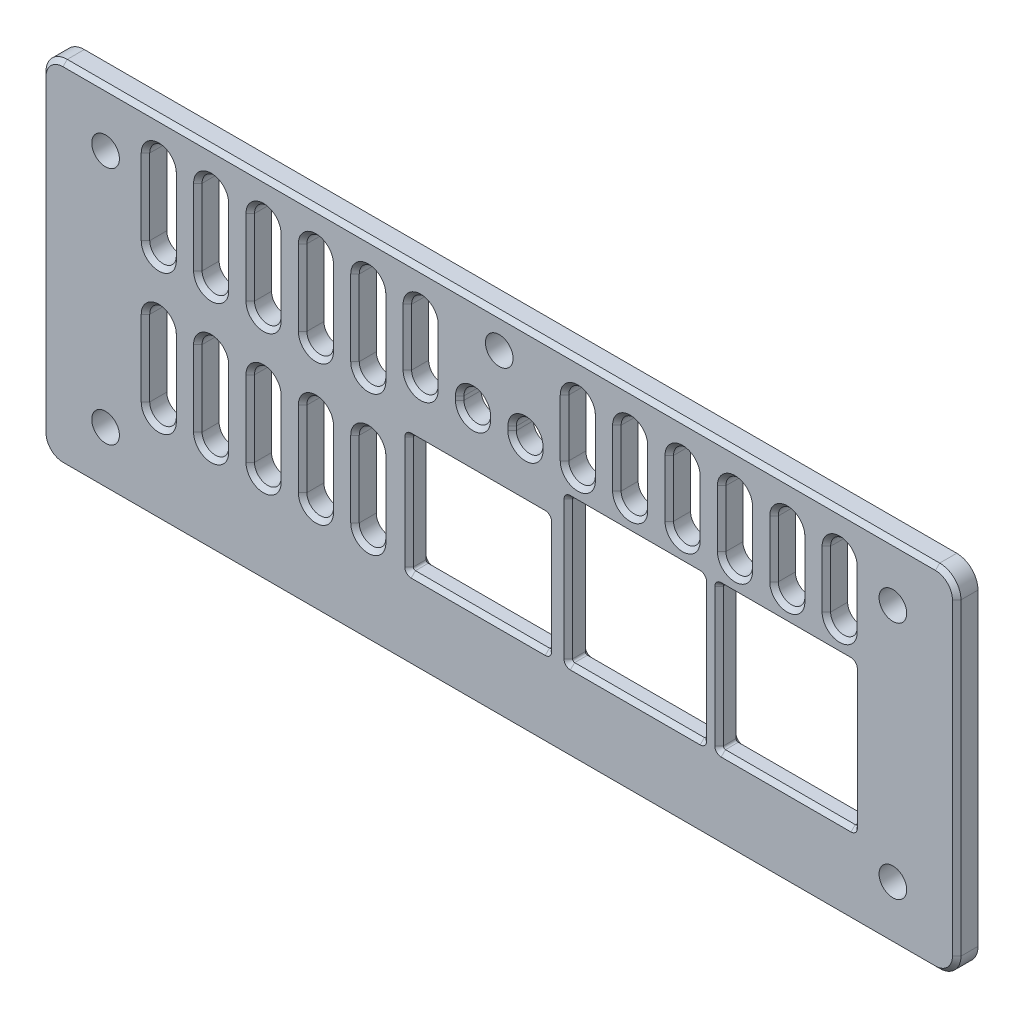
SolidWorks part; units mm, degrees
ref_plane "Plane XZ" through (0, 0, 0) normal (0, 0, 1) x (1, 0, 0)
ref_plane "Plane XY" through (0, 0, 0) normal (0, 1, 0) x (1, 0, 0)
ref_plane "Plane YZ" through (0, 0, 0) normal (1, 0, 0) x (0, 0, -1)
sketch "Sketch1" plane through (0, 0, 0) normal (0, 0, 1) x (1, 0, 0)
  line L0 (-55.88, -14.2875) -> (55.88, -14.2875) construction
  line L1 (-55.88, 22.225) -> (55.88, 22.225) construction
  line L2 (-55.88, 22.225) -> (-55.88, -22.225) construction
  line L3 (-55.88, -22.225) -> (55.88, -22.225) construction
  line L4 (55.88, 22.225) -> (55.88, -22.225) construction
  line L5 (0, 0) -> (0, -14.2875) construction
  line L6 (0, 0) -> (-55.88, 0) construction
  line L7 (-54.61, 20.955) -> (54.61, 20.955)
  line L8 (54.61, 20.955) -> (54.61, -20.955)
  line L9 (-54.61, -20.955) -> (54.61, -20.955)
  line L10 (-54.61, 20.955) -> (-54.61, -20.955)
  dimension "D1" = 111.76
  dimension "D2" = 44.45
  dimension "D3" = 14.2875
  dimension "D4" = 1.27
extrude "Boss-Extrude1" add sketch "Sketch1" along normal blind 2.54
sketch "Sketch4" plane through (0, 0, 2.54) normal (0, 0, 1) x (1, 0, 0)
  line L0 (-46.99, 0) -> (46.99, 0) construction
  line L1 (-46.99, 14.2875) -> (46.99, 14.2875) construction
  line L2 (-46.99, 14.2875) -> (-46.99, -14.2875) construction
  line L3 (-46.99, -14.2875) -> (46.99, -14.2875) construction
  line L4 (46.99, 14.2875) -> (46.99, -14.2875) construction
  circle A0 centre (-46.99, 14.2875) radius 1.651
  circle A1 centre (-46.99, -14.2875) radius 1.651
  circle A2 centre (46.99, -14.2875) radius 1.651
  circle A3 centre (46.99, 14.2875) radius 1.651
  dimension "D1" = 3.302
  dimension "D4" = 3.302
  dimension "D2" = 93.98
  dimension "D3" = 28.575
extrude "Cut-Extrude2" cut sketch "Sketch4" against normal through all and the other way through all
fillet "Fillet1" radius 2.54 4 edges at (54.61, 20.955, 1.27) (54.61, -20.955, 1.27) (-54.61, -20.955, 1.27) (-54.61, 20.955, 1.27)
sketch "Sketch3" plane through (0, 0, 2.54) normal (0, 0, 1) x (1, 0, 0)
  line L0 (15.24, -11.1252) -> (15.24, -12.3825) construction
  line L1 (-12.76, -11.1252) -> (43.24, -11.1252) construction
  line L2 (-12.76, -11.1252) -> (-12.76, -12.3825) construction
  line L3 (-12.76, -12.3825) -> (43.24, -12.3825) construction
  line L4 (43.24, -11.1252) -> (43.24, -12.3825) construction
  line L5 (-55.88, -14.2875) -> (55.88, -14.2875) construction
  line L6 (16.24, 5.8928) -> (16.24, -11.1252) construction
  line L7 (8.239, 5.8928) -> (24.241, 5.8928)
  line L8 (8.239, 5.8928) -> (8.239, -11.1252)
  line L9 (8.239, -11.1252) -> (24.241, -11.1252)
  line L10 (24.241, 5.8928) -> (24.241, -11.1252)
  line L11 (26.239, 5.8928) -> (42.241, 5.8928)
  line L12 (26.239, 5.8928) -> (26.239, -11.1252)
  line L13 (26.239, -11.1252) -> (42.241, -11.1252)
  line L14 (42.241, 5.8928) -> (42.241, -11.1252)
  line L15 (-10.765, 2.8448) -> (5.745, 2.8448)
  line L16 (-10.765, 2.8448) -> (-10.765, -11.1252)
  line L17 (-10.765, -11.1252) -> (5.745, -11.1252)
  line L18 (5.745, 2.8448) -> (5.745, -11.1252)
  line L19 (34.24, 5.8928) -> (34.24, -11.1252) construction
  line L20 (-2.51, 2.8448) -> (-2.51, -11.1252) construction
  point P27 (26.239, -2.6162)
  dimension "D1" = 15.24
  dimension "D2" = 1.905
  dimension "D3" = 1.2573
  dimension "D4" = 56
  dimension "D5" = 17.018
  dimension "D6" = 16.002
  dimension "D7" = 16.51
  dimension "D8" = 13.97
  dimension "D9" = 29
  dimension "D10" = 47
  dimension "D11" = 10.25
  dimension "D12" = 1.998
extrude "RPi 3 Cutout" cut sketch "Sketch3" against normal through all
sketch "Sketch14" plane through (0, 0, 2.54) normal (0, 0, 1) x (1, 0, 0)
  circle A0 centre (0, 17.145) radius 1.651
  dimension "D2" = 3.302
  dimension "D1" = 17.145
extrude "Cut-Extrude8" cut sketch "Sketch14" against normal through all
sketch "Sketch15" plane through (0, 0, 2.54) normal (0, 0, 1) x (1, 0, 0)
  line L0 (40.64, 9.3853) -> (40.64, 16.1925) construction
  line L1 (54.61, 0) -> (50.3635, 0) construction
  line L2 (50.3635, -17.78) -> (-15.1531, -17.78) construction
  line L3 (50.3635, -17.78) -> (50.3635, 17.78) construction
  line L4 (50.3635, 17.78) -> (-15.1531, 17.78) construction
  line L5 (-15.1531, -17.78) -> (-15.1531, 17.78) construction
  line L6 (54.61, -18.415) -> (54.61, 18.415) construction
  line L7 (39.0525, 9.3853) -> (39.0525, 16.1925)
  line L8 (42.2275, 9.3853) -> (42.2275, 16.1925)
  line L9 (-15.1531, 7.7978) -> (50.3635, 7.7978) construction
  line L10 (-15.6308, 9.3853) -> (-15.6308, 16.1925) construction
  line L11 (34.3877, 9.3853) -> (34.3877, 16.1925) construction
  line L12 (32.8002, 9.3853) -> (32.8002, 16.1925)
  line L13 (35.9752, 9.3853) -> (35.9752, 16.1925)
  line L14 (28.1354, 9.3853) -> (28.1354, 16.1925) construction
  line L15 (26.5479, 9.3853) -> (26.5479, 16.1925)
  line L16 (29.7229, 9.3853) -> (29.7229, 16.1925)
  line L17 (21.8831, 9.3853) -> (21.8831, 16.1925) construction
  line L18 (20.2956, 9.3853) -> (20.2956, 16.1925)
  line L19 (23.4706, 9.3853) -> (23.4706, 16.1925)
  line L20 (15.6308, 9.3853) -> (15.6308, 16.1925) construction
  line L21 (14.0433, 9.3853) -> (14.0433, 16.1925)
  line L22 (17.2183, 9.3853) -> (17.2183, 16.1925)
  line L23 (9.3785, 9.3853) -> (9.3785, 16.1925) construction
  line L24 (7.791, 9.3853) -> (7.791, 16.1925)
  line L25 (10.966, 9.3853) -> (10.966, 16.1925)
  line L26 (3.1262, 9.3853) -> (3.1262, 16.1925) construction
  line L27 (1.5387, 9.3853) -> (1.5387, 16.1925) construction
  line L28 (4.7137, 9.3853) -> (4.7137, 16.1925) construction
  line L29 (-3.1262, 9.3853) -> (-3.1262, 16.1925) construction
  line L30 (-4.7137, 9.3853) -> (-4.7137, 16.1925) construction
  line L31 (-1.5387, 9.3853) -> (-1.5387, 16.1925) construction
  line L32 (-9.3785, 9.3853) -> (-9.3785, 16.1925) construction
  line L33 (-10.966, 9.3853) -> (-10.966, 16.1925)
  line L34 (-7.791, 9.3853) -> (-7.791, 16.1925)
  line L35 (-3.1262, 9.3853) -> (-3.1262, 9.849) construction
  line L36 (-4.7137, 9.3853) -> (-4.7137, 9.849)
  line L37 (-1.5387, 9.3853) -> (-1.5387, 9.849)
  line L38 (3.1262, 9.3853) -> (3.1262, 9.849) construction
  line L39 (1.5387, 9.3853) -> (1.5387, 9.849)
  line L40 (4.7137, 9.3853) -> (4.7137, 9.849)
  line L41 (-17.2183, 9.3853) -> (-17.2183, 16.1925)
  line L42 (-14.0433, 9.3853) -> (-14.0433, 16.1925)
  line L43 (-21.8831, 9.3853) -> (-21.8831, 16.1925) construction
  line L44 (-23.4706, 9.3853) -> (-23.4706, 16.1925)
  line L45 (-20.2956, 9.3853) -> (-20.2956, 16.1925)
  line L46 (-28.1354, 9.3853) -> (-28.1354, 16.1925) construction
  line L47 (-29.7229, 9.3853) -> (-29.7229, 16.1925)
  line L48 (-26.5479, 9.3853) -> (-26.5479, 16.1925)
  line L49 (-34.3877, 9.3853) -> (-34.3877, 16.1925) construction
  line L50 (-35.9752, 9.3853) -> (-35.9752, 16.1925)
  line L51 (-32.8002, 9.3853) -> (-32.8002, 16.1925)
  line L52 (-40.64, 9.3853) -> (-40.64, 16.1925) construction
  line L53 (-42.2275, 9.3853) -> (-42.2275, 16.1925)
  line L54 (-39.0525, 9.3853) -> (-39.0525, 16.1925)
  circle A0 centre (46.99, 14.2875) radius 4.7625 construction
  arc A1 (39.0525, 9.3853) -> (42.2275, 9.3853) centre (40.64, 9.3853) ccw
  arc A2 (42.2275, 16.1925) -> (39.0525, 16.1925) centre (40.64, 16.1925) ccw
  arc A3 (32.8002, 9.3853) -> (35.9752, 9.3853) centre (34.3877, 9.3853) ccw
  arc A4 (35.9752, 16.1925) -> (32.8002, 16.1925) centre (34.3877, 16.1925) ccw
  arc A5 (26.5479, 9.3853) -> (29.7229, 9.3853) centre (28.1354, 9.3853) ccw
  arc A6 (29.7229, 16.1925) -> (26.5479, 16.1925) centre (28.1354, 16.1925) ccw
  arc A7 (20.2956, 9.3853) -> (23.4706, 9.3853) centre (21.8831, 9.3853) ccw
  arc A8 (23.4706, 16.1925) -> (20.2956, 16.1925) centre (21.8831, 16.1925) ccw
  arc A9 (14.0433, 9.3853) -> (17.2183, 9.3853) centre (15.6308, 9.3853) ccw
  arc A10 (17.2183, 16.1925) -> (14.0433, 16.1925) centre (15.6308, 16.1925) ccw
  arc A11 (7.791, 9.3853) -> (10.966, 9.3853) centre (9.3785, 9.3853) ccw
  arc A12 (10.966, 16.1925) -> (7.791, 16.1925) centre (9.3785, 16.1925) ccw
  arc A13 (1.5387, 9.3853) -> (4.7137, 9.3853) centre (3.1262, 9.3853) ccw construction
  arc A14 (4.7137, 16.1925) -> (1.5387, 16.1925) centre (3.1262, 16.1925) ccw construction
  arc A15 (-4.7137, 9.3853) -> (-1.5387, 9.3853) centre (-3.1262, 9.3853) ccw construction
  arc A16 (-1.5387, 16.1925) -> (-4.7137, 16.1925) centre (-3.1262, 16.1925) ccw construction
  arc A17 (-10.966, 9.3853) -> (-7.791, 9.3853) centre (-9.3785, 9.3853) ccw
  arc A18 (-7.791, 16.1925) -> (-10.966, 16.1925) centre (-9.3785, 16.1925) ccw
  circle A19 centre (0, 17.145) radius 6.35 construction
  arc A20 (-4.7137, 9.3853) -> (-1.5387, 9.3853) centre (-3.1262, 9.3853) ccw
  arc A21 (-1.5387, 9.849) -> (-4.7137, 9.849) centre (-3.1262, 9.849) ccw
  arc A22 (1.5387, 9.3853) -> (4.7137, 9.3853) centre (3.1262, 9.3853) ccw
  arc A23 (4.7137, 9.849) -> (1.5387, 9.849) centre (3.1262, 9.849) ccw
  circle A24 centre (-46.99, 14.2875) radius 4.7625 construction
  arc A25 (-17.2183, 9.3853) -> (-14.0433, 9.3853) centre (-15.6308, 9.3853) ccw
  arc A26 (-14.0433, 16.1925) -> (-17.2183, 16.1925) centre (-15.6308, 16.1925) ccw
  arc A27 (-23.4706, 9.3853) -> (-20.2956, 9.3853) centre (-21.8831, 9.3853) ccw
  arc A28 (-20.2956, 16.1925) -> (-23.4706, 16.1925) centre (-21.8831, 16.1925) ccw
  arc A29 (-29.7229, 9.3853) -> (-26.5479, 9.3853) centre (-28.1354, 9.3853) ccw
  arc A30 (-26.5479, 16.1925) -> (-29.7229, 16.1925) centre (-28.1354, 16.1925) ccw
  arc A31 (-35.9752, 9.3853) -> (-32.8002, 9.3853) centre (-34.3877, 9.3853) ccw
  arc A32 (-32.8002, 16.1925) -> (-35.9752, 16.1925) centre (-34.3877, 16.1925) ccw
  arc A33 (-42.2275, 9.3853) -> (-39.0525, 9.3853) centre (-40.64, 9.3853) ccw
  arc A34 (-39.0525, 16.1925) -> (-42.2275, 16.1925) centre (-40.64, 16.1925) ccw
  point P13 (40.64, 12.7889)
  point P25 (34.3877, 12.7889)
  point P32 (28.1354, 12.7889)
  point P39 (21.8831, 12.7889)
  point P46 (15.6308, 12.7889)
  point P53 (9.3785, 12.7889)
  point P60 (3.1262, 12.7889)
  point P67 (-3.1262, 12.7889)
  point P74 (-9.3785, 12.7889)
  point P83 (-3.1262, 9.6172)
  point P88 (3.1262, 9.6172)
  point P98 (-15.6308, 12.7889)
  point P105 (-21.8831, 12.7889)
  point P112 (-28.1354, 12.7889)
  point P119 (-34.3877, 12.7889)
  point P126 (-40.64, 12.7889)
  dimension "D1" = 9.525
  dimension "D7" = 12.7
  dimension "D2" = 35.56
  dimension "D3" = 7.7978
  dimension "D4" = 3.175
  dimension "D6" = 3.0773
  dimension "D5" = 14
extrude "Cut-Extrude9" cut sketch "Sketch15" against normal through all
sketch "Sketch22" plane through (0, 0, 2.54) normal (0, 0, 1) x (1, 0, 0)
  line L0 (-40.64, -9.5377) -> (-40.64, -0.4826) construction
  line L1 (-42.2275, -9.5377) -> (-42.2275, -0.4826)
  line L2 (-39.0525, -9.5377) -> (-39.0525, -0.4826)
  line L3 (-40.64, 7.1374) -> (-40.64, 16.1925) construction
  line L4 (-42.2275, 7.1374) -> (-42.2275, 16.1925)
  line L5 (-39.0525, 7.1374) -> (-39.0525, 16.1925)
  line L6 (-54.61, 3.3274) -> (54.61, 3.3274) construction
  line L9 (-34.3877, -9.5377) -> (-34.3877, -0.4826) construction
  line L10 (-35.9752, -9.5377) -> (-35.9752, -0.4826)
  line L11 (-32.8002, -9.5377) -> (-32.8002, -0.4826)
  line L12 (-34.3877, 7.1374) -> (-34.3877, 16.1925) construction
  line L13 (-35.9752, 7.1374) -> (-35.9752, 16.1925)
  line L14 (-32.8002, 7.1374) -> (-32.8002, 16.1925)
  line L15 (-28.1354, -9.5377) -> (-28.1354, -0.4826) construction
  line L16 (-29.7229, -9.5377) -> (-29.7229, -0.4826)
  line L17 (-26.5479, -9.5377) -> (-26.5479, -0.4826)
  line L18 (-28.1354, 7.1374) -> (-28.1354, 16.1925) construction
  line L19 (-29.7229, 7.1374) -> (-29.7229, 16.1925)
  line L20 (-26.5479, 7.1374) -> (-26.5479, 16.1925)
  line L21 (-21.8831, -9.5377) -> (-21.8831, -0.4826) construction
  line L22 (-23.4706, -9.5377) -> (-23.4706, -0.4826)
  line L23 (-20.2956, -9.5377) -> (-20.2956, -0.4826)
  line L24 (-21.8831, 7.1374) -> (-21.8831, 16.1925) construction
  line L25 (-23.4706, 7.1374) -> (-23.4706, 16.1925)
  line L26 (-20.2956, 7.1374) -> (-20.2956, 16.1925)
  line L27 (-15.6308, -9.5377) -> (-15.6308, -0.4826) construction
  line L28 (-17.2183, -9.5377) -> (-17.2183, -0.4826)
  line L29 (-14.0433, -9.5377) -> (-14.0433, -0.4826)
  line L30 (-15.6308, 7.1374) -> (-15.6308, 16.1925) construction
  line L31 (-17.2183, 7.1374) -> (-17.2183, 16.1925)
  line L32 (-14.0433, 7.1374) -> (-14.0433, 16.1925)
  line L33 (5.745, -11.1252) -> (-45.2211, -11.1252) construction
  arc A0 (-42.2275, -9.5377) -> (-39.0525, -9.5377) centre (-40.64, -9.5377) ccw
  arc A1 (-39.0525, -0.4826) -> (-42.2275, -0.4826) centre (-40.64, -0.4826) ccw
  arc A2 (-42.2275, 7.1374) -> (-39.0525, 7.1374) centre (-40.64, 7.1374) ccw
  arc A3 (-39.0525, 16.1925) -> (-42.2275, 16.1925) centre (-40.64, 16.1925) ccw
  arc A4 (-39.0525, 16.1925) -> (-42.2275, 16.1925) centre (-40.64, 16.1925) ccw construction
  arc A5 (-35.9752, -9.5377) -> (-32.8002, -9.5377) centre (-34.3877, -9.5377) ccw
  arc A6 (-32.8002, -0.4826) -> (-35.9752, -0.4826) centre (-34.3877, -0.4826) ccw
  arc A7 (-35.9752, 7.1374) -> (-32.8002, 7.1374) centre (-34.3877, 7.1374) ccw
  arc A8 (-32.8002, 16.1925) -> (-35.9752, 16.1925) centre (-34.3877, 16.1925) ccw
  arc A9 (-29.7229, -9.5377) -> (-26.5479, -9.5377) centre (-28.1354, -9.5377) ccw
  arc A10 (-26.5479, -0.4826) -> (-29.7229, -0.4826) centre (-28.1354, -0.4826) ccw
  arc A11 (-29.7229, 7.1374) -> (-26.5479, 7.1374) centre (-28.1354, 7.1374) ccw
  arc A12 (-26.5479, 16.1925) -> (-29.7229, 16.1925) centre (-28.1354, 16.1925) ccw
  arc A13 (-23.4706, -9.5377) -> (-20.2956, -9.5377) centre (-21.8831, -9.5377) ccw
  arc A14 (-20.2956, -0.4826) -> (-23.4706, -0.4826) centre (-21.8831, -0.4826) ccw
  arc A15 (-23.4706, 7.1374) -> (-20.2956, 7.1374) centre (-21.8831, 7.1374) ccw
  arc A16 (-20.2956, 16.1925) -> (-23.4706, 16.1925) centre (-21.8831, 16.1925) ccw
  arc A17 (-17.2183, -9.5377) -> (-14.0433, -9.5377) centre (-15.6308, -9.5377) ccw
  arc A18 (-14.0433, -0.4826) -> (-17.2183, -0.4826) centre (-15.6308, -0.4826) ccw
  arc A19 (-17.2183, 7.1374) -> (-14.0433, 7.1374) centre (-15.6308, 7.1374) ccw
  arc A20 (-14.0433, 16.1925) -> (-17.2183, 16.1925) centre (-15.6308, 16.1925) ccw
  arc A21 (-32.8002, 16.1925) -> (-35.9752, 16.1925) centre (-34.3877, 16.1925) ccw construction
  point P2 (-40.64, -5.0102)
  point P7 (-40.64, 11.6649)
  point P26 (-34.3877, -5.0102)
  point P31 (-34.3877, 11.6649)
  point P40 (-28.1354, -5.0102)
  point P45 (-28.1354, 11.6649)
  point P54 (-21.8831, -5.0102)
  point P59 (-21.8831, 11.6649)
  point P68 (-15.6308, -5.0102)
  point P73 (-15.6308, 11.6649)
  dimension "D1" = 3.81
  dimension "D2" = 5
extrude "Cut-Extrude15" cut sketch "Sketch22" against normal through all
fillet "Fillet3" radius 0.254 12 edges at (24.241, 5.8928, 1.27) (42.241, 5.8928, 1.27) (24.241, -11.1252, 1.27) (42.241, -11.1252, 1.27) (8.239, -11.1252, 1.27) (26.239, -11.1252, 1.27) (-10.765, -11.1252, 1.27) (8.239, 5.8928, 1.27) (26.239, 5.8928, 1.27) (-10.765, 2.8448, 1.27) (5.745, 2.8448, 1.27) (5.745, -11.1252, 1.27)
chamfer "Chamfer2" distance 0.508 angle 45 24 edges at (16.24, -11.1252, 0) (24.1666, -11.0508, 0) (8.3134, -11.0508, 0) (24.241, -2.6162, 0) (8.239, -2.6162, 0) (24.1666, 5.8184, 0) (8.3134, 5.8184, 0) (16.24, 5.8928, 0) (34.24, -11.1252, 0) (42.1666, -11.0508, 0) (26.3134, -11.0508, 0) (42.241, -2.6162, 0) (26.239, -2.6162, 0) (42.1666, 5.8184, 0) (26.3134, 5.8184, 0) (34.24, 5.8928, 0) (-2.51, -11.1252, 0) (5.6706, -11.0508, 0) (-10.6906, -11.0508, 0) (5.745, -4.1402, 0) (-10.765, -4.1402, 0) (5.6706, 2.7704, 0) (-10.6906, 2.7704, 0) (-2.51, 2.8448, 0)
chamfer "Chamfer3" distance 0.508 angle 45 108 edges at (34.24, -11.1252, 2.54) (42.1666, -11.0508, 2.54) (26.3134, -11.0508, 2.54) (42.241, -2.6162, 2.54) (26.239, -2.6162, 2.54) (42.1666, 5.8184, 2.54) (26.3134, 5.8184, 2.54) (34.24, 5.8928, 2.54) (16.24, -11.1252, 2.54) (24.1666, -11.0508, 2.54) (8.3134, -11.0508, 2.54) (24.241, -2.6162, 2.54) (8.239, -2.6162, 2.54) (24.1666, 5.8184, 2.54) (8.3134, 5.8184, 2.54) (16.24, 5.8928, 2.54) (40.64, 7.7978, 2.54) (42.2275, 12.7889, 2.54) (39.0525, 12.7889, 2.54) (40.64, 17.78, 2.54) (34.3877, 7.7978, 2.54) (35.9752, 12.7889, 2.54) (32.8002, 12.7889, 2.54) (34.3877, 17.78, 2.54) (28.1354, 7.7978, 2.54) (29.7229, 12.7889, 2.54) (26.5479, 12.7889, 2.54) (28.1354, 17.78, 2.54) (21.8831, 7.7978, 2.54) (23.4706, 12.7889, 2.54) (20.2956, 12.7889, 2.54) (21.8831, 17.78, 2.54) (15.6308, 7.7978, 2.54) (17.2183, 12.7889, 2.54) (14.0433, 12.7889, 2.54) (15.6308, 17.78, 2.54) (9.3785, 7.7978, 2.54) (10.966, 12.7889, 2.54) (7.791, 12.7889, 2.54) (9.3785, 17.78, 2.54) (3.1262, 7.7978, 2.54) (4.7137, 9.6172, 2.54) (1.5387, 9.6172, 2.54) (3.1262, 11.4365, 2.54) (-3.1262, 7.7978, 2.54) (-1.5387, 9.6172, 2.54) (-4.7137, 9.6172, 2.54) (-3.1262, 11.4365, 2.54) (-9.3785, 7.7978, 2.54) (-7.791, 12.7889, 2.54) (-10.966, 12.7889, 2.54) (-9.3785, 17.78, 2.54) (-2.51, -11.1252, 2.54) (5.6706, -11.0508, 2.54) (-10.6906, -11.0508, 2.54) (5.745, -4.1402, 2.54) (-10.765, -4.1402, 2.54) (5.6706, 2.7704, 2.54) (-10.6906, 2.7704, 2.54) (-2.51, 2.8448, 2.54) (-40.64, -11.1252, 2.54) (-39.0525, -5.0102, 2.54) (-42.2275, -5.0102, 2.54) (-40.64, 1.1049, 2.54) (-34.3877, -11.1252, 2.54) (-32.8002, -5.0102, 2.54) (-35.9752, -5.0102, 2.54) (-34.3877, 1.1049, 2.54) (-28.1354, -11.1252, 2.54) (-26.5479, -5.0102, 2.54) (-29.7229, -5.0102, 2.54) (-28.1354, 1.1049, 2.54) (-21.8831, -11.1252, 2.54) (-20.2956, -5.0102, 2.54) (-23.4706, -5.0102, 2.54) (-21.8831, 1.1049, 2.54) (-15.6308, -11.1252, 2.54) (-14.0433, -5.0102, 2.54) (-17.2183, -5.0102, 2.54) (-15.6308, 1.1049, 2.54) (-15.6308, 5.5499, 2.54) (-14.0433, 11.6649, 2.54) (-17.2183, 11.6649, 2.54) (-15.6308, 17.78, 2.54) (-21.8831, 5.5499, 2.54) (-20.2956, 11.6649, 2.54) (-23.4706, 11.6649, 2.54) (-21.8831, 17.78, 2.54) (-28.1354, 5.5499, 2.54) (-26.5479, 11.6649, 2.54) (-29.7229, 11.6649, 2.54) (-28.1354, 17.78, 2.54) (-34.3877, 5.5499, 2.54) (-32.8002, 11.6649, 2.54) (-35.9752, 11.6649, 2.54) (-34.3877, 17.78, 2.54) (-40.64, 5.5499, 2.54) (-39.0525, 11.6649, 2.54) (-42.2275, 11.6649, 2.54) (-40.64, 17.78, 2.54) (54.61, 0, 2.54) (53.8661, 20.2111, 2.54) (53.8661, -20.2111, 2.54) (0, 20.955, 2.54) (0, -20.955, 2.54) (-53.8661, 20.2111, 2.54) (-53.8661, -20.2111, 2.54) (-54.61, 0, 2.54)
